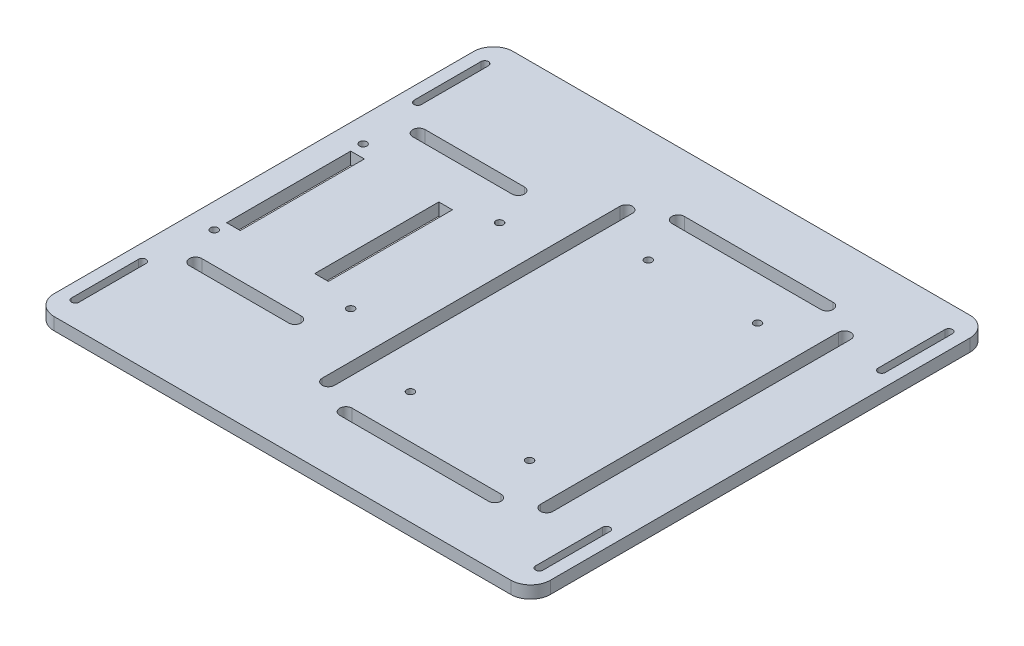
SolidWorks part; units mm, degrees
ref_plane "Front Plane" through (0, 0, 0) normal (0, 0, 1) x (1, 0, 0)
ref_plane "Top Plane" through (0, 0, 0) normal (0, 1, 0) x (1, 0, 0)
ref_plane "Right Plane" through (0, 0, 0) normal (1, 0, 0) x (0, 0, -1)
sketch "Sketch2" plane through (0, 0, 0) normal (0, 1, 0) x (1, 0, 0)
  line L0 (-93.5, 55.5) -> (-93.5, 82.5) construction
  line L1 (-100, -92.5) -> (100, -92.5)
  line L2 (-100, -92.5) -> (-100, 92.5)
  line L3 (-100, 92.5) -> (100, 92.5)
  line L4 (100, -92.5) -> (100, 92.5)
  line L5 (-100, -92.5) -> (100, 92.5) construction
  line L6 (-100, 92.5) -> (100, -92.5) construction
  line L7 (-95, 55.5) -> (-95, 82.5)
  line L8 (-92, 55.5) -> (-92, 82.5)
  line L9 (-100, 0) -> (100, 0) construction
  line L10 (100, 0) -> (0, 92.5) construction
  line L11 (0, 92.5) -> (0, -92.5) construction
  line L12 (93.5, 55.5) -> (93.5, 82.5) construction
  line L13 (95, 55.5) -> (95, 82.5)
  line L14 (92, 55.5) -> (92, 82.5)
  line L15 (93.5, -55.5) -> (93.5, -82.5) construction
  line L16 (95, -55.5) -> (95, -82.5)
  line L17 (92, -55.5) -> (92, -82.5)
  line L18 (-93.5, -55.5) -> (-93.5, -82.5) construction
  line L19 (-95, -55.5) -> (-95, -82.5)
  line L20 (-92, -55.5) -> (-92, -82.5)
  arc A0 (-95, 55.5) -> (-92, 55.5) centre (-93.5, 55.5) ccw
  arc A1 (-92, 82.5) -> (-95, 82.5) centre (-93.5, 82.5) ccw
  arc A2 (95, 55.5) -> (92, 55.5) centre (93.5, 55.5) cw
  arc A3 (92, 82.5) -> (95, 82.5) centre (93.5, 82.5) cw
  arc A4 (95, -55.5) -> (92, -55.5) centre (93.5, -55.5) ccw
  arc A5 (92, -82.5) -> (95, -82.5) centre (93.5, -82.5) ccw
  arc A6 (-95, -55.5) -> (-92, -55.5) centre (-93.5, -55.5) cw
  arc A7 (-92, -82.5) -> (-95, -82.5) centre (-93.5, -82.5) cw
  point P0 (0, 0)
  point P8 (-93.5, 69)
  point P19 (93.5, 69)
  point P26 (93.5, -69)
  point P33 (-93.5, -69)
  dimension "D4" = 1.5
  dimension "D1" = 200
  dimension "D2" = 185
  dimension "D3" = 27
  dimension "D5" = 5
  dimension "D6" = 10
extrude "Boss-Extrude1" add sketch "Sketch2" along normal blind 5
sketch "Sketch3" plane through (0, 5, 0) normal (0, 1, 0) x (1, 0, 0)
  line L0 (-100, 0) -> (100, 0) construction
  line L1 (-100, 92.5) -> (-100, -92.5) construction
  line L2 (100, -92.5) -> (100, 92.5) construction
  line L3 (100, 0) -> (0, -92.5) construction
  line L4 (-100, -92.5) -> (100, -92.5) construction
  line L5 (0, -92.5) -> (0, 92.5) construction
  line L6 (100, 92.5) -> (-100, 92.5) construction
  line L7 (-62.5, -35) -> (-62.5, 55.3864) construction
  line L8 (-30, -35) -> (-95, -35)
  line L9 (-30, -35) -> (-30, 35)
  line L10 (-30, 35) -> (-95, 35)
  line L11 (-95, -35) -> (-95, 35)
  line L12 (-30, -35) -> (-95, 35) construction
  line L13 (-30, 35) -> (-95, -35) construction
  line L14 (-82.5, 45) -> (-42.5, 45) construction
  line L15 (-82.5, 47.5) -> (-42.5, 47.5)
  line L16 (-82.5, 42.5) -> (-42.5, 42.5)
  line L17 (-82.5, -45) -> (-42.5, -45) construction
  line L18 (-82.5, -47.5) -> (-42.5, -47.5)
  line L19 (-82.5, -42.5) -> (-42.5, -42.5)
  line L21 (-90, -25) -> (-84.5, -25)
  line L22 (-90, -25) -> (-90, 25)
  line L23 (-90, 25) -> (-84.5, 25)
  line L24 (-84.5, -25) -> (-84.5, 25)
  line L25 (-90, -25) -> (-84.5, 25) construction
  line L26 (-90, 25) -> (-84.5, -25) construction
  line L27 (-54.5, -25) -> (-49, -25)
  line L28 (-54.5, -25) -> (-54.5, 25)
  line L29 (-54.5, 25) -> (-49, 25)
  line L30 (-49, -25) -> (-49, 25)
  line L31 (-54.5, -25) -> (-49, 25) construction
  line L32 (-54.5, 25) -> (-49, -25) construction
  circle A0 centre (-90, -30) radius 1.5
  circle A1 centre (-90, 30) radius 1.5
  circle A2 centre (-35, 30) radius 1.5
  circle A3 centre (-35, -30) radius 1.5
  arc A4 (-82.5, 47.5) -> (-82.5, 42.5) centre (-82.5, 45) ccw
  arc A5 (-42.5, 42.5) -> (-42.5, 47.5) centre (-42.5, 45) ccw
  arc A6 (-82.5, -47.5) -> (-82.5, -42.5) centre (-82.5, -45) cw
  arc A7 (-42.5, -42.5) -> (-42.5, -47.5) centre (-42.5, -45) cw
  point P9 (-62.5, 0)
  point P29 (-62.5, 45)
  point P36 (-62.5, -45)
  point P41 (-87.25, 0)
  point P46 (-51.75, 0)
  dimension "D4" = 3
  dimension "D8" = 2.5
  dimension "D1" = 65
  dimension "D2" = 70
  dimension "D3" = 5
  dimension "D5" = 5
  dimension "D6" = 5
  dimension "D7" = 40
  dimension "D9" = 10
  dimension "D10" = 5.5
  dimension "D11" = 50
  dimension "D12" = 10
  dimension "D13" = 50
  dimension "D14" = 5.5
  dimension "D15" = 30
extrude "Cut-Extrude1" cut sketch "Sketch3" against normal through all contours L16 A5 L15 A4 | A7 L19 A6 L18 | L21 L24 L23 L22 | L27 L30 L29 L28 | A0 | A1 | A3 | A2
sketch "Sketch4" plane through (0, 5, 0) normal (0, 1, 0) x (1, 0, 0)
  line L0 (-100, 0) -> (100, 0) construction
  line L1 (-100, 92.5) -> (-100, -92.5) construction
  line L2 (100, -92.5) -> (100, 92.5) construction
  line L3 (30, 92.5) -> (30, -92.5) construction
  line L4 (100, 92.5) -> (-100, 92.5) construction
  line L5 (-100, -92.5) -> (100, -92.5) construction
  line L6 (74, -60) -> (74, 60) construction
  line L7 (71.5, -60) -> (71.5, 60)
  line L8 (76.5, -60) -> (76.5, 60)
  line L9 (-14, -60) -> (-14, 60) construction
  line L10 (-16.5, -60) -> (-16.5, 60)
  line L11 (-11.5, -60) -> (-11.5, 60)
  line L12 (0, 66.935) -> (60, 66.935) construction
  line L13 (0, 69.435) -> (60, 69.435)
  line L14 (0, 64.435) -> (60, 64.435)
  line L15 (0, -66.935) -> (60, -66.935) construction
  line L16 (0, -69.435) -> (60, -69.435)
  line L17 (0, -64.435) -> (60, -64.435)
  circle A0 centre (8, 46.935) radius 1.5
  circle A1 centre (52, 46.935) radius 1.5
  circle A2 centre (6, -46.935) radius 1.5
  circle A3 centre (54, -46.935) radius 1.5
  arc A4 (71.5, -60) -> (76.5, -60) centre (74, -60) ccw
  arc A5 (76.5, 60) -> (71.5, 60) centre (74, 60) ccw
  arc A6 (-16.5, -60) -> (-11.5, -60) centre (-14, -60) ccw
  arc A7 (-11.5, 60) -> (-16.5, 60) centre (-14, 60) ccw
  arc A8 (0, 69.435) -> (0, 64.435) centre (0, 66.935) ccw
  arc A9 (60, 64.435) -> (60, 69.435) centre (60, 66.935) ccw
  arc A10 (0, -69.435) -> (0, -64.435) centre (0, -66.935) cw
  arc A11 (60, -64.435) -> (60, -69.435) centre (60, -66.935) cw
  point P22 (74, 0)
  point P29 (-14, 0)
  point P37 (30, 66.935)
  point P44 (30, -66.935)
  dimension "D1" = 3
  dimension "D4" = 3
  dimension "D7" = 46.935
  dimension "D8" = 2.5
  dimension "D12" = 2.5
  dimension "D15" = 2.5
  dimension "D2" = 70
  dimension "D3" = 44
  dimension "D5" = 48
  dimension "D6" = 93.87
  dimension "D9" = 120
  dimension "D10" = 20
  dimension "D11" = 120
  dimension "D13" = 20
  dimension "D14" = 60
  dimension "D16" = 20
extrude "Cut-Extrude3" cut sketch "Sketch4" against normal through all
fillet "Fillet1" radius 8 4 edges at (100, 2.5, -92.5) (100, 2.5, 92.5) (-100, 2.5, -92.5) (-100, 2.5, 92.5)
